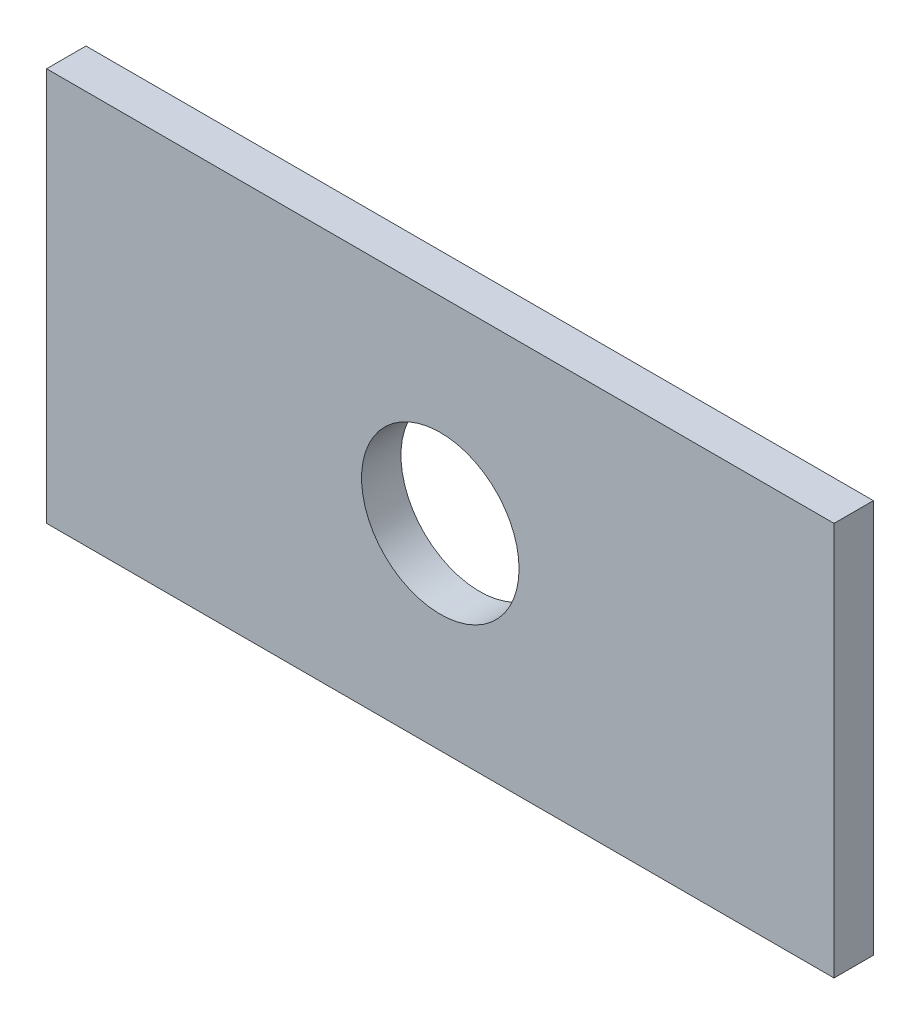
SolidWorks part; units mm, degrees
material "AISI 321 退火不鏽鋼 (SS)"
ref_plane "Front" through (0, 0, 0) normal (0, 0, 1) x (1, 0, 0)
ref_plane "Top" through (0, 0, 0) normal (0, 1, 0) x (1, 0, 0)
ref_plane "Right" through (0, 0, 0) normal (1, 0, 0) x (0, 0, -1)
sketch "Sketch1" plane through (0, 0, 0) normal (0, 0, 1) x (1, 0, 0)
  line L0 (-124.9729, 0) -> (125.3881, 0) construction
  line L1 (0, 79.3017) -> (0, -103.7981) construction
  line L2 (100, -50) -> (100, 50)
  line L3 (-100, 50) -> (100, 50)
  line L4 (-100, -50) -> (-100, 50)
  line L5 (-100, -50) -> (100, -50)
  dimension "D1" = 200
  dimension "D2" = 100
extrude "Extrude1" add sketch "Sketch1" along normal blind 10
sketch "Sketch2" plane through (0, 0, 10) normal (0, 0, 1) x (1, 0, 0)
  circle A0 centre (0, 0) radius 20
  dimension "D1" = 40
extrude "Cut-Extrude1" cut sketch "Sketch2" against normal through all
